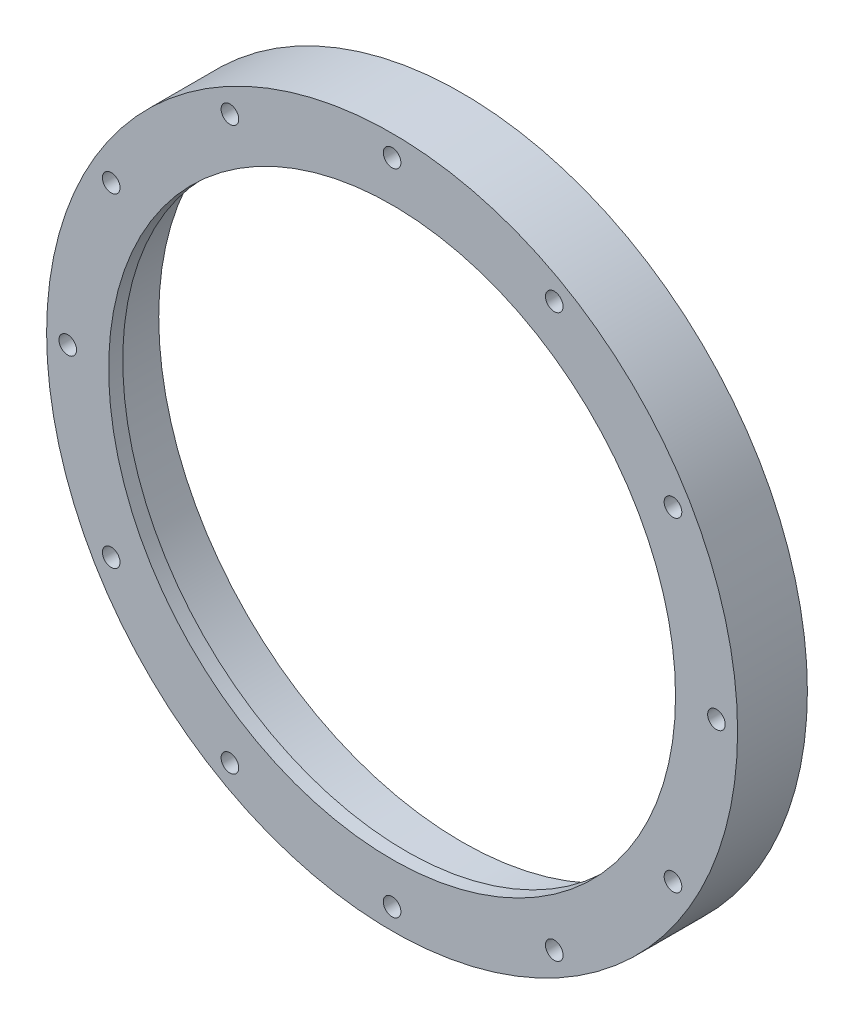
SolidWorks part; units mm, degrees
material "6061 合金"
ref_plane "前视基准面" through (0, 0, 0) normal (0, 0, 1) x (1, 0, 0)
ref_plane "上视基准面" through (0, 0, 0) normal (0, 1, 0) x (1, 0, 0)
ref_plane "右视基准面" through (0, 0, 0) normal (1, 0, 0) x (0, 0, -1)
sketch "草图1" plane through (0, 0, 0) normal (0, 0, 1) x (1, 0, 0)
  circle A0 centre (0, 0) radius 43
  circle A1 centre (0, 0) radius 49
  dimension "D1" = 86
  dimension "D2" = 6
extrude "凸台-拉伸1" add sketch "草图1" along normal blind 7.9
sketch "草图2" plane through (0, 0, 0) normal (0, 0, -1) x (-1, 0, 0)
  circle A1 centre (0, 0) radius 56
  circle A2 centre (0, 0) radius 40.2
  circle A3 centre (0, 0) radius 40.2
  circle A4 centre (0, 0) radius 49 construction
  dimension "D2" = 7
  dimension "D1" = 2.8
extrude "凸台-拉伸2" [suppressed] add sketch "草图2" along normal blind 4
sketch "草图3" plane through (0, 0, 7.9) normal (0, 0, 1) x (1, 0, 0)
  circle A1 centre (0, 0) radius 49 construction
  circle A2 centre (0, 0) radius 40.2
  circle A3 centre (0, 0) radius 40.2
  circle A4 centre (0, 0) radius 49
  dimension "D1" = 2.8
extrude "凸台-拉伸3" add sketch "草图3" along normal blind 2
sketch "草图5" plane through (0, 0, 0) normal (0, 0, -1) x (-1, 0, 0)
  circle A0 centre (0, 0) radius 46 construction
  circle A2 centre (0, 0) radius 49 construction
  dimension "D1" = 3
hole_wizard "M3 螺纹孔1" positions "草图6" profile "草图7" tap size "M3" standard "GB" end condition up to next
sketch "草图6" plane through (0, 0, 0) normal (0, 0, -1) x (-1, 0, 0)
  circle A0 centre (0, 0) radius 46 construction
  point P0 (0, 46)
sketch "草图7" plane through (0, 46, 0) normal (1, 0, 0) x (0, 1, 0)
  line L0 (0, 0) -> (0, 9.9)
  line L1 (0, 9.9) -> (1.25, 9.9)
  line L2 (1.25, 9.9) -> (1.25, 0)
  line L5 (1.25, 0) -> (0, 0)
  line L11 (0, -6.35) -> (0, 107.95) construction
  dimension "通孔螺纹孔钻头直径" = 2.5
  dimension "通孔螺纹孔钻头深度" = 9.9
cosmetic thread "孔螺蚊线1" parameters "D2"=3
pattern_circular "阵列(圆周)1" count 12 over 360 about axis through (0, 0, 0) along (0, 0, 1) of "M3 螺纹孔1"
cosmetic thread "孔螺蚊线2" parameters "D2"=3
cosmetic thread "孔螺蚊线3" parameters "D2"=3
cosmetic thread "孔螺蚊线4" parameters "D2"=3
cosmetic thread "孔螺蚊线5" parameters "D2"=3
cosmetic thread "孔螺蚊线6" parameters "D2"=3
cosmetic thread "孔螺蚊线7" parameters "D2"=3
cosmetic thread "孔螺蚊线8" parameters "D2"=3
cosmetic thread "孔螺蚊线9" parameters "D2"=3
cosmetic thread "孔螺蚊线10" parameters "D2"=3
cosmetic thread "孔螺蚊线11" parameters "D2"=3
cosmetic thread "孔螺蚊线12" parameters "D2"=3
